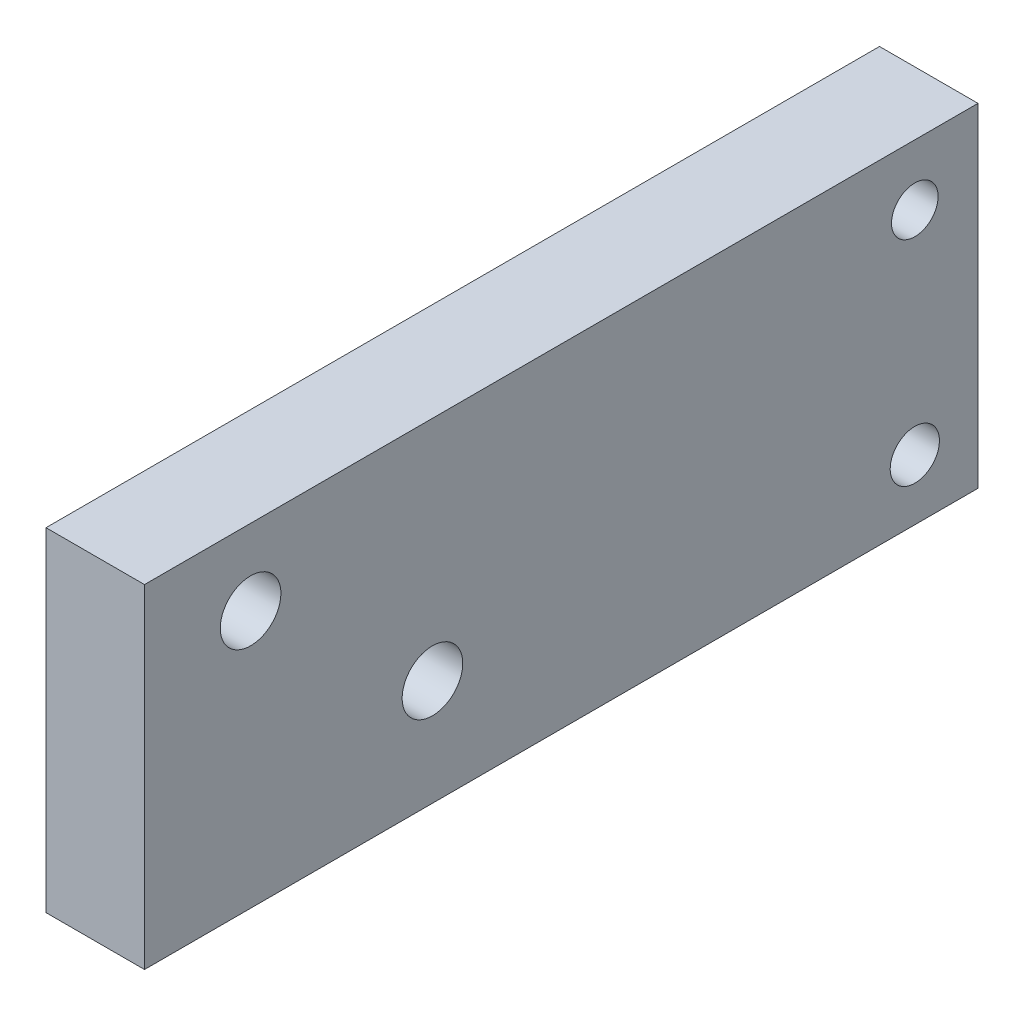
SolidWorks part; units mm, degrees
ref_plane "Plan de face" through (0, 0, 0) normal (0, 0, 1) x (1, 0, 0)
ref_plane "Plan de dessus" through (0, 0, 0) normal (0, 1, 0) x (1, 0, 0)
ref_plane "Plan de droite" through (0, 0, 0) normal (1, 0, 0) x (0, 0, -1)
sketch "Esquisse1" plane through (0, 0, 0) normal (0, 0, 1) x (1, 0, 0)
  line L1 (0, 0) -> (24.25, 0)
  line L2 (0, 0) -> (0, 16)
  line L3 (0, 16) -> (24.25, 16)
  line L4 (24.25, 0) -> (24.25, 16)
  line L5 (0, 0) -> (24.25, 0)
  line L6 (0, 0) -> (0, -24)
  line L7 (0, -24) -> (24.25, -24)
  line L8 (24.25, 0) -> (24.25, -24)
  line L9 (4, 16) -> (24.25, 16)
  line L10 (4, 16) -> (4, 2)
  line L11 (4, 2) -> (24.25, 2)
  line L12 (24.25, 16) -> (24.25, 2)
  line L13 (0, -24) -> (20.25, -24)
  line L14 (0, -24) -> (0, -2)
  line L15 (0, -2) -> (20.25, -2)
  line L16 (20.25, -24) -> (20.25, -2)
  dimension "D1" = 24.25
  dimension "D2" = 16
  dimension "D3" = 24
  dimension "D4" = 22
  dimension "D5" = 14
  dimension "D6" = 4
  dimension "D7" = 4
extrude "Boss.-Extru.1" add sketch "Esquisse1" along normal blind 20 contours L11 L10 L3 L2 L1 L4 | L16 L7 L8 L1 L6 L15
sketch "Esquisse3" plane through (0, 0, 0) normal (0, 0, -1) x (-1, 0, 0)
  line L1 (-4, 16) -> (0, 16)
  line L2 (-4, 16) -> (-4, -2)
  line L3 (-4, -2) -> (0, -2)
  line L4 (0, 16) -> (0, -2)
extrude "Boss.-Extru.2" add sketch "Esquisse3" along normal blind 20
sketch "Esquisse4" plane through (0, 0, 20) normal (0, 0, 1) x (1, 0, 0)
  line L1 (0, 16) -> (4, 16)
  line L2 (0, 16) -> (0, -2)
  line L3 (0, -2) -> (4, -2)
  line L4 (4, 16) -> (4, -2)
extrude "Boss.-Extru.3" add sketch "Esquisse4" along normal blind 20
sketch "Esquisse5" plane through (0, 0, 0) normal (-1, 0, 0) x (0, 0, 1)
  line L0 (40, 16) -> (-20, 16) construction
  line L1 (0, -2) -> (20, -2)
  line L2 (0, -2) -> (0, 16)
  line L3 (0, 16) -> (20, 16)
  line L4 (20, -2) -> (20, 16)
  line L5 (40, -2) -> (-20, -2) construction
  line L6 (20, 16) -> (23.65, 16)
  line L7 (20, 16) -> (20, -2)
  line L8 (20, -2) -> (23.65, -2)
  line L9 (23.65, 16) -> (23.65, -2)
  line L11 (23.65, 16) -> (40, 16)
  line L12 (23.65, 16) -> (23.65, -2)
  line L13 (23.65, -2) -> (40, -2)
  line L14 (40, 16) -> (40, -2)
  line L15 (0, 16) -> (-2.35, 16)
  line L16 (0, 16) -> (0, -2)
  line L17 (0, -2) -> (-2.35, -2)
  line L18 (-2.35, 16) -> (-2.35, -2)
  line L19 (-2.35, 16) -> (-20, 16)
  line L20 (-2.35, 16) -> (-2.35, -2)
  line L21 (-2.35, -2) -> (-20, -2)
  line L22 (-20, 16) -> (-20, -2)
  circle A0 centre (4.65, 5) radius 2
  circle A1 centre (16.65, 15) radius 2
  point P22 (0, 0)
  line M8 (40, 16) -> (-20, 16)
  line M9 (-20, 16) -> (-20, -2)
  line M10 (-20, -2) -> (40, -2)
  line M11 (40, -2) -> (40, 16)
  dimension "D4" = 4
  dimension "D5" = 4
  dimension "D1" = 20
  dimension "D2" = 7
  dimension "D3" = 10
  dimension "D6" = 4.65
  dimension "D7" = 12
  dimension "D8" = 2.35
  dimension "D9" = 7
extrude "Enlèv. mat.-Extru.1" cut sketch "Esquisse5" against normal blind 20 contours L18 M8 M9 M10 | L9 M8 M10 M11 | A1 | A0
sketch "Esquisse6" plane through (0, 16, 0) normal (0, 1, 0) x (1, 0, 0)
  line L1 (0, 2.35) -> (4, 2.35)
  line L2 (0, 2.35) -> (0, -23.65)
  line L3 (0, -23.65) -> (4, -23.65)
  line L4 (4, 2.35) -> (4, -23.65)
extrude "Boss.-Extru.4" add sketch "Esquisse6" along normal blind 4
sketch "Esquisse7" plane through (0, 0, 0) normal (-1, 0, 0) x (0, 0, 1)
  circle A0 centre (16.65, 15) radius 2
extrude "Enlèv. mat.-Extru.2" cut sketch "Esquisse7" against normal blind 4
sketch "Esquisse8" plane through (20.25, 0, 0) normal (-1, 0, 0) x (0, 0, 1)
  line L0 (23.65, -2) -> (-2.35, -2) construction
  line L2 (20, -24) -> (20, -2) construction
  circle A0 centre (20, -7) radius 2
  circle A1 centre (20, -20) radius 2
  dimension "D1" = 4
  dimension "D2" = 4
  dimension "D3" = 5
  dimension "D4" = 13
  dimension "D5" = 0
  dimension "D6" = 0
extrude "Enlèv. mat.-Extru.3" cut sketch "Esquisse8" against normal blind 4 contours A0 | A1
sketch "Esquisse9" plane through (0, 0, 20) normal (0, 0, 1) x (1, 0, 0)
  line L1 (20.25, -24) -> (24.25, -24)
  line L2 (20.25, -24) -> (20.25, 2)
  line L3 (20.25, 2) -> (24.25, 2)
  line L4 (24.25, -24) -> (24.25, 2)
extrude "Boss.-Extru.5" add sketch "Esquisse9" along normal blind 8
sketch "Esquisse11" plane through (20.25, 0, 0) normal (-1, 0, 0) x (0, 0, 1)
  line L0 (20, -5) -> (20, -9) construction
  line L1 (0, -2) -> (28, -2)
  line L2 (0, -2) -> (0, -24)
  line L3 (0, -24) -> (28, -24)
  line L4 (28, -2) -> (28, -24)
  line L5 (20, -18) -> (20, -22) construction
  line L6 (14, -24) -> (0, -2)
  circle A0 centre (20, -7) radius 2
  circle A1 centre (20, -20) radius 2
  line M3 (0, -2) -> (0, -24)
  line M4 (0, -24) -> (28, -24)
  line M7 (20, -5) -> (20, -9)
  line M10 (20, -18) -> (20, -22)
extrude "Enlèv. mat.-Extru.5" cut sketch "Esquisse11" against normal blind 8 contours A0 M7 | A1 M10 | L6 M4 M3
sketch "Esquisse13" plane through (0, 2, 0) normal (0, 1, 0) x (1, 0, 0)
  line L1 (4, 0) -> (24.25, 0)
  line L2 (4, 0) -> (4, -28)
  line L3 (4, -28) -> (24.25, -28)
  line L4 (24.25, 0) -> (24.25, -28)
extrude "Enlèv. mat.-Extru.7" cut sketch "Esquisse13" against normal through all
sketch "Esquisse14" plane through (4, 0, 0) normal (1, 0, 0) x (0, 0, -1)
  line L1 (2.35, -2) -> (31.35, -2)
  line L2 (2.35, -2) -> (2.35, 20)
  line L3 (2.35, 20) -> (31.35, 20)
  line L4 (31.35, -2) -> (31.35, 20)
  circle A0 centre (27.18, 16) radius 1.5371
  circle A1 centre (-4.65, 5) radius 2 construction
  circle A2 centre (27.18, 2) radius 1.6248
  dimension "D1" = 22
  dimension "D2" = 31.83
  dimension "D3" = 29
  dimension "D4" = 4
  dimension "D5" = 4
  dimension "D6" = 31.83
extrude "Boss.-Extru.6" add sketch "Esquisse14" against normal blind 6.5
sketch "Esquisse15" plane through (0, 0, 0) normal (-1, 0, 0) x (0, 0, 1)
  line L1 (-2.35, 20) -> (23.65, 20)
  line L2 (-2.35, 20) -> (-2.35, -2)
  line L3 (-2.35, -2) -> (23.65, -2)
  line L4 (23.65, 20) -> (23.65, -2)
  circle A0 centre (4.65, 5) radius 2
  circle A1 centre (16.65, 15) radius 2
extrude "Boss.-Extru.7" add sketch "Esquisse15" along normal blind 2.5
